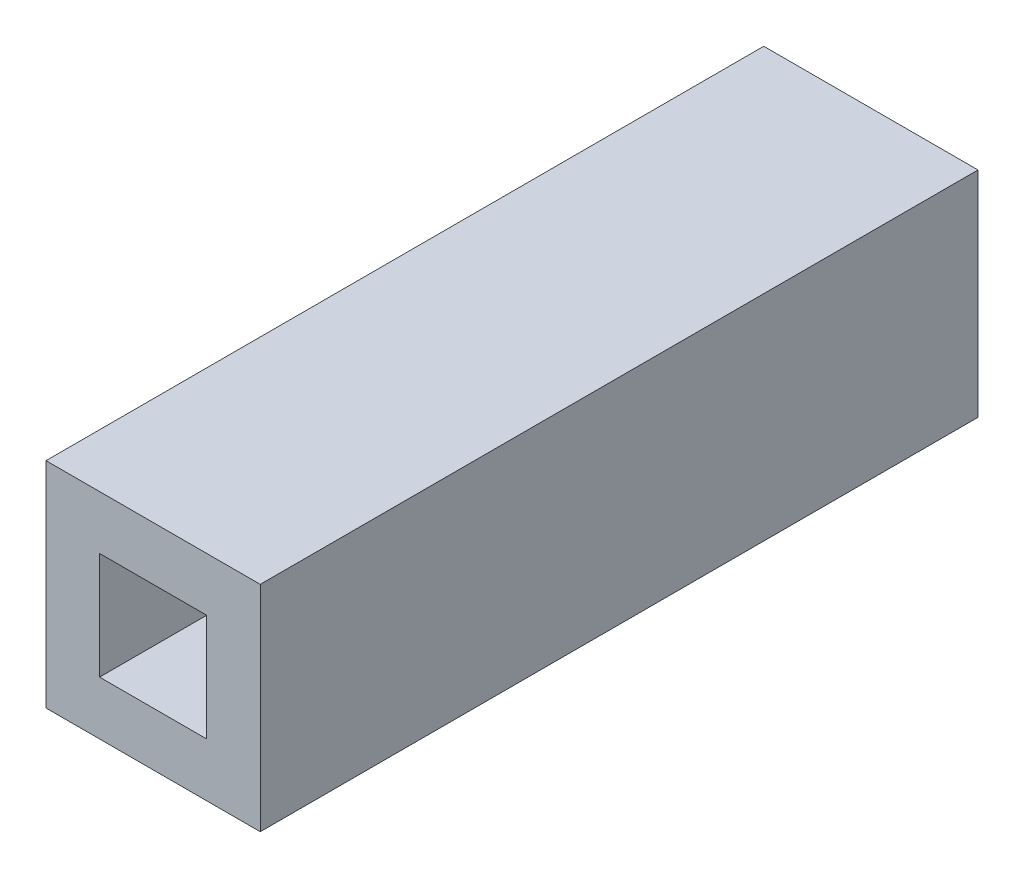
SolidWorks part; units mm, degrees
material "6063-O"
ref_plane "Front Plane" through (0, 0, 0) normal (0, 0, 1) x (1, 0, 0)
ref_plane "Top Plane" through (0, 0, 0) normal (0, 1, 0) x (1, 0, 0)
ref_plane "Right Plane" through (0, 0, 0) normal (1, 0, 0) x (0, 0, -1)
sketch "Sketch1" plane through (0, 0, 0) normal (0, 0, 1) x (1, 0, 0)
  line L1 (-10, -10) -> (10, -10)
  line L2 (-10, -10) -> (-10, 10)
  line L3 (-10, 10) -> (10, 10)
  line L4 (10, -10) -> (10, 10)
  line L5 (-10, -10) -> (10, 10) construction
  line L6 (-10, 10) -> (10, -10) construction
  point P0 (0, 0)
  dimension "D1" = 20
extrude "Extrude-Thin1" add sketch "Sketch1" along normal blind 67 thin thin type one direction reverse wall 5
